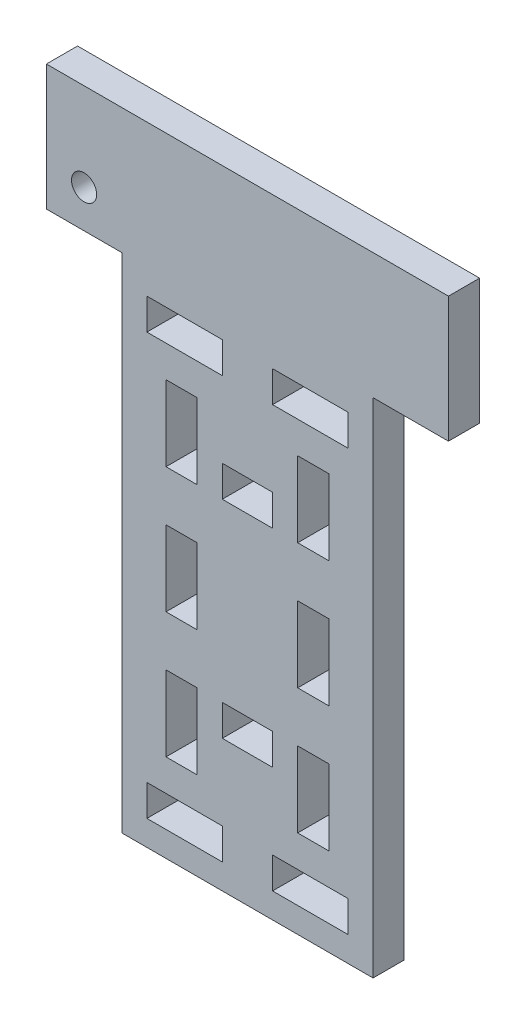
SolidWorks part; units mm, degrees
ref_plane "Front Plane" through (0, 0, 0) normal (0, 0, 1) x (1, 0, 0)
ref_plane "Top Plane" through (0, 0, 0) normal (0, 1, 0) x (1, 0, 0)
ref_plane "Right Plane" through (0, 0, 0) normal (1, 0, 0) x (0, 0, -1)
sketch "Model" plane through (0, 0, 0) normal (0, 0, 1) x (1, 0, 0)
  line L81 (50, 200) -> (80, 200)
  line L82 (50, 0) -> (-50, 0)
  line L83 (50, 0) -> (50, 200)
  line L84 (-50, 100) -> (50, 100) construction
  line L85 (-50, 0) -> (-50, 200)
  line L86 (-80, 250) -> (80, 250)
  line L87 (-80, 250) -> (-80, 200)
  line L88 (-80, 200) -> (-50, 200)
  line L89 (80, 250) -> (80, 200)
  line L90 (0, 0) -> (0, 250) construction
  line L91 (-32.4, 135) -> (-20, 135)
  line L92 (-32.4, 85) -> (-20, 85)
  line L93 (-32.4, 85) -> (-32.4, 115)
  line L94 (-32.4, 115) -> (-20, 115)
  line L95 (-20, 85) -> (-20, 115)
  line L96 (-32.4, 85) -> (-20, 115) construction
  line L97 (-32.4, 115) -> (-20, 85) construction
  line L98 (-20, 135) -> (-20, 165)
  line L99 (-32.4, 165) -> (-20, 165)
  line L100 (-32.4, 135) -> (-32.4, 165)
  line L101 (-32.4, 35) -> (-32.4, 65)
  line L102 (-32.4, 65) -> (-20, 65)
  line L103 (-20, 35) -> (-20, 65)
  line L104 (-32.4, 35) -> (-20, 35)
  line L105 (32.4, 115) -> (20, 85) construction
  line L106 (32.4, 85) -> (20, 115) construction
  line L107 (32.4, 35) -> (20, 35)
  line L108 (20, 35) -> (20, 65)
  line L109 (32.4, 65) -> (20, 65)
  line L110 (32.4, 35) -> (32.4, 65)
  line L111 (32.4, 135) -> (32.4, 165)
  line L112 (32.4, 165) -> (20, 165)
  line L113 (20, 135) -> (20, 165)
  line L114 (20, 85) -> (20, 115)
  line L115 (32.4, 115) -> (20, 115)
  line L116 (32.4, 85) -> (32.4, 115)
  line L117 (32.4, 85) -> (20, 85)
  line L118 (32.4, 135) -> (20, 135)
  line L119 (-10, 65) -> (10, 52.6) construction
  line L120 (-10, 147.4) -> (10, 147.4)
  line L121 (-10, 147.4) -> (-10, 135)
  line L122 (-10, 135) -> (10, 135)
  line L123 (10, 147.4) -> (10, 135)
  line L124 (-10, 147.4) -> (10, 135) construction
  line L125 (-10, 135) -> (10, 147.4) construction
  line L126 (-10, 52.6) -> (10, 65) construction
  line L127 (10, 52.6) -> (10, 65)
  line L128 (-10, 65) -> (10, 65)
  line L129 (-10, 52.6) -> (-10, 65)
  line L130 (-10, 52.6) -> (10, 52.6)
  line L131 (40, 10) -> (10, 10)
  line L132 (-40, 22.4) -> (-10, 22.4)
  line L133 (-40, 22.4) -> (-40, 10)
  line L134 (-40, 10) -> (-10, 10)
  line L135 (-10, 22.4) -> (-10, 10)
  line L136 (40, 22.4) -> (40, 10)
  line L137 (40, 22.4) -> (10, 22.4)
  line L138 (10, 22.4) -> (10, 10)
  line L139 (40, 190) -> (10, 190)
  line L140 (40, 177.6) -> (40, 190)
  line L141 (40, 177.6) -> (10, 177.6)
  line L142 (10, 177.6) -> (10, 190)
  line L143 (-10, 177.6) -> (-10, 190)
  line L144 (-40, 190) -> (-10, 190)
  line L145 (-40, 177.6) -> (-40, 190)
  line L146 (-40, 177.6) -> (-10, 177.6)
  circle A10 centre (-65, 215) radius 5
  point P80 (-26.2, 100)
  point P138 (26.2, 100)
  point P139 (0, 141.2)
  point P148 (0, 58.8)
  dimension "D18" = 10
  dimension "D1" = 100
  dimension "D3" = 50
  dimension "D4" = 30
  dimension "D5" = 12.4
  dimension "D7" = 30
  dimension "D9" = 20
  dimension "D11" = 20
  dimension "D6" = 40
  dimension "D12" = 12.4
  dimension "D13" = 20
  dimension "D2" = 200
  dimension "D14" = 12.4
  dimension "D15" = 30
  dimension "D16" = 10
  dimension "D17" = 10
  dimension "D19" = 15
  dimension "D20" = 15
  dimension "D8" = 2
  dimension "D10" = 2
extrude "Boss-Extrude1" add sketch "Model" along normal blind 12.4
equation "\"tab-width-large\"= 30mm ' Width of the large version of the Tab"
equation "\"tab-width-small\"= 20mm ' Width of the small version of the Tab"
equation "\"material-thickness\"= 12.4mm"
equation "\"plate-supporttab-gapheight\"= 20mm"
equation "\"plate-supporttab-gapwidth\"= 40mm"
equation "\"yplate-width\"= 100mm"
equation "\"yplate-height\"= 200mm"
equation "\"D7@Model\"=\"tab-width-large\""
equation "\"D9@Model\"= \"plate-supporttab-gapheight\""
equation "\"D1@Boss-Extrude1\"=\"material-thickness\""
equation "\"D5@Model\"=\"material-thickness\""
equation "\"D11@Model\"=\"plate-supporttab-gapheight\""
equation "\"D6@Model\"=\"plate-supporttab-gapwidth\""
equation "\"D12@Model\"=\"material-thickness\""
equation "\"D13@Model\"=\"tab-width-small\""
equation "\"D2@Model\"=\"yplate-height\""
equation "\"D1@Model\"=\"yplate-width\""
equation "\"D14@Model\"=\"material-thickness\""
equation "\"D15@Model\"=\"tab-width-large\""
